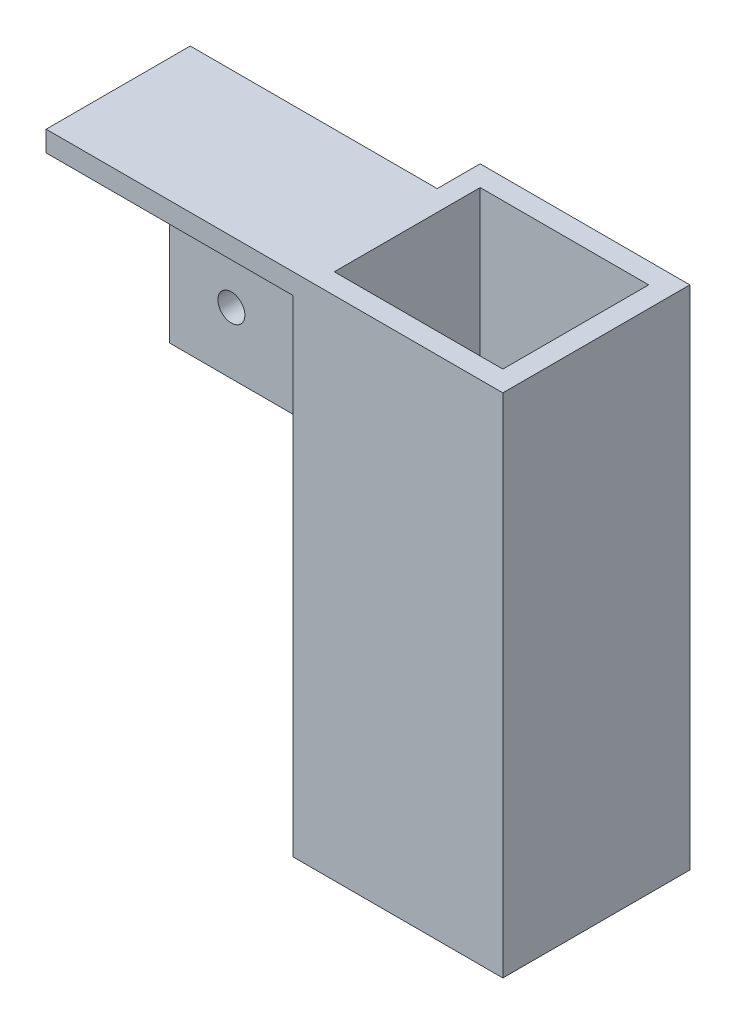
SolidWorks part; units mm, degrees
ref_plane "Front Plane" through (0, 0, 0) normal (0, 0, 1) x (1, 0, 0)
ref_plane "Top Plane" through (0, 0, 0) normal (0, 1, 0) x (1, 0, 0)
ref_plane "Right Plane" through (0, 0, 0) normal (1, 0, 0) x (0, 0, -1)
sketch "Sketch1" plane through (0, 0, 0) normal (0, 1, 0) x (1, 0, 0)
  line L1 (-38.1, 19.05) -> (38.1, 19.05)
  line L2 (-38.1, 19.05) -> (-38.1, -19.05)
  line L3 (-38.1, -19.05) -> (38.1, -19.05)
  line L5 (-38.1, 19.05) -> (38.1, -19.05) construction
  line L6 (-38.1, -19.05) -> (38.1, 19.05) construction
  line L8 (38.1, 19.05) -> (38.1, -19.05)
  point P0 (0, 0)
  point P6 (0, 0)
  dimension "D1" = 76.2
  dimension "D2" = 38.1
extrude "Boss-Extrude1" add sketch "Sketch1" along normal blind 6.35
sketch "Sketch2" plane through (0, 0, -19.05) normal (0, 0, -1) x (-1, 0, 0)
  line L0 (-19.05, -12.7) -> (-19.05, -50.8) construction
  line L1 (38.1, 6.35) -> (-38.1, 6.35)
  line L2 (38.1, 6.35) -> (38.1, -69.85)
  line L3 (38.1, -69.85) -> (-38.1, -69.85)
  line L4 (-38.1, 6.35) -> (-38.1, -69.85)
  line L5 (19.05, -12.7) -> (19.05, -50.8) construction
  line L6 (-19.05, -31.75) -> (19.05, -31.75) construction
  circle A0 centre (-19.05, -12.7) radius 4.1656
  circle A1 centre (19.05, -12.7) radius 4.1656
  circle A2 centre (19.05, -50.8) radius 4.1656
  circle A3 centre (-19.05, -50.8) radius 4.1656
  point P12 (0, -31.75)
  point P16 (-38.1, -31.75)
  dimension "D5" = 8.3312
  dimension "D1" = 76.2
  dimension "D2" = 76.2
  dimension "D3" = 38.1
  dimension "D4" = 38.1
extrude "Boss-Extrude2" add sketch "Sketch2" along normal blind 6.35
sketch "Sketch3" plane through (0, 6.35, 0) normal (0, 1, 0) x (1, 0, 0)
  line L5 (44.45, -12.7) -> (44.45, 32.3)
  line L10 (38.1, -19.05) -> (102.8, -19.05)
  line L11 (38.1, -19.05) -> (38.1, 38.65)
  line L12 (38.1, 38.65) -> (102.8, 38.65)
  line L13 (102.8, -19.05) -> (102.8, 38.65)
  line L14 (44.45, 32.3) -> (96.45, 32.3)
  line L15 (96.45, -12.7) -> (96.45, 32.3)
  line L16 (44.45, -12.7) -> (96.45, -12.7)
  point P5 (111.5908, 50.736)
  point P6 (48.6385, -4.8962)
  dimension "D1" = 6.35
  dimension "D2" = 52
  dimension "D3" = 45
extrude "Boss-Extrude3" add sketch "Sketch3" against normal blind 150
sketch "Sketch4" plane through (0, -143.65, 0) normal (0, -1, 0) x (1, 0, 0)
  line L4 (38.1, 19.05) -> (38.1, -38.65)
  line L5 (38.1, -38.65) -> (102.8, -38.65)
  line L6 (102.8, -38.65) -> (102.8, 19.05)
  line L7 (102.8, 19.05) -> (38.1, 19.05)
  line L8 (38.1, 19.05) -> (38.1, -38.65)
  line L9 (38.1, -38.65) -> (102.8, -38.65)
  line L10 (102.8, -38.65) -> (102.8, 19.05)
  line L11 (102.8, 19.05) -> (38.1, 19.05)
  dimension "D1" = 0
extrude "Boss-Extrude4" add sketch "Sketch4" along normal blind 6.35
